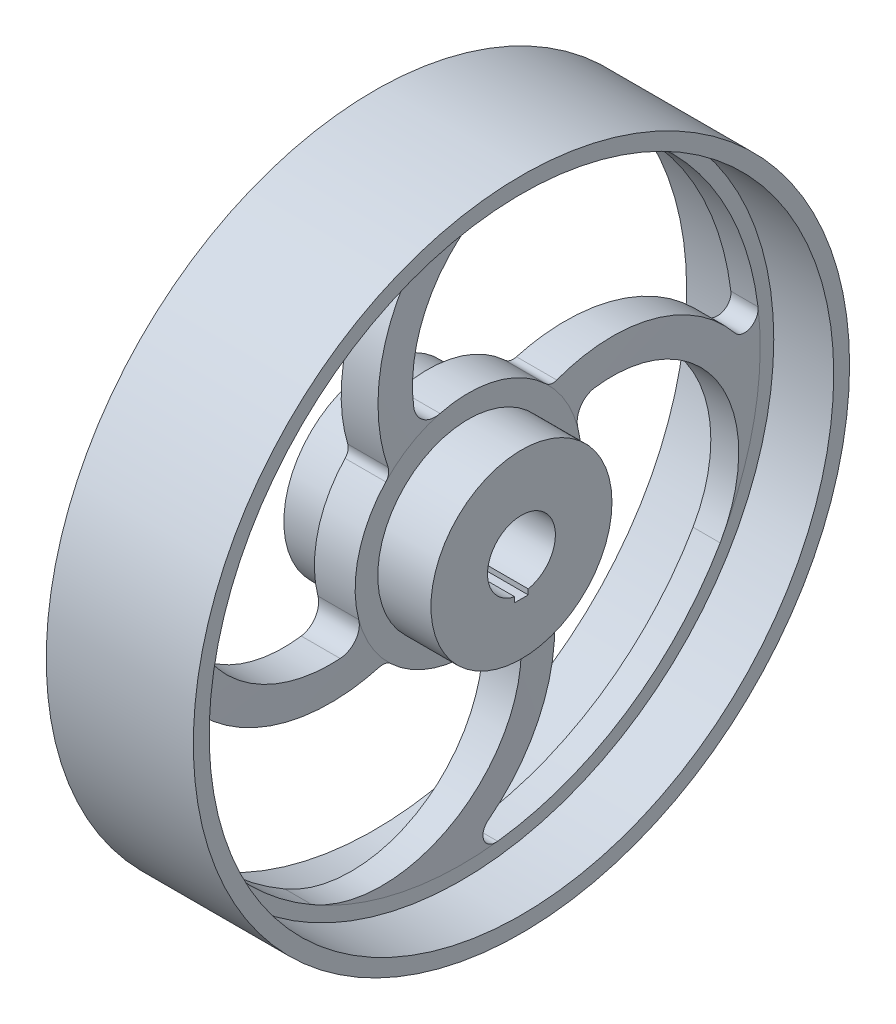
SolidWorks part; units mm, degrees
ref_plane "Front Plane" through (0, 0, 0) normal (0, 0, 1) x (1, 0, 0)
ref_plane "Top Plane" through (0, 0, 0) normal (0, 1, 0) x (1, 0, 0)
ref_plane "Right Plane" through (0, 0, 0) normal (1, 0, 0) x (0, 0, -1)
sketch "Sketch1" plane through (0, 0, 0) normal (0, 0, 1) x (1, 0, 0)
  line L0 (-32.5, 0) -> (32.5, 0)
  line L1 (-32.5, 15) -> (32.5, 15)
  line L2 (0, 0) -> (0, 138) construction
  line L3 (32.5, 15) -> (-32.5, 15)
  line L4 (32.5, 15) -> (32.5, 40)
  line L5 (32.5, 40) -> (-32.5, 40)
  line L6 (-32.5, 15) -> (-32.5, 40)
  line L7 (9, 30) -> (-9, 30)
  line L8 (9, 30) -> (9, 50)
  line L9 (9, 50) -> (-9, 50)
  line L10 (-9, 30) -> (-9, 50)
  line L11 (9, 30) -> (-9, 50) construction
  line L12 (9, 50) -> (-9, 30) construction
  line L13 (-6, 132) -> (-9, 50)
  line L14 (-32.5, 138) -> (32.5, 138)
  line L15 (-32.5, 138) -> (-32.5, 145)
  line L16 (-32.5, 145) -> (32.5, 145)
  line L17 (32.5, 138) -> (32.5, 145)
  line L18 (-32.5, 138) -> (32.5, 145) construction
  line L19 (-32.5, 145) -> (32.5, 138) construction
  line L20 (6, 144) -> (-6, 144)
  line L21 (6, 144) -> (6, 132)
  line L22 (6, 132) -> (-6, 132)
  line L23 (-6, 144) -> (-6, 132)
  line L24 (6, 144) -> (-6, 132) construction
  line L25 (6, 132) -> (-6, 144) construction
  line L26 (6, 132) -> (9, 50)
  point P4 (0, 0)
  point P9 (0, 40)
  point P14 (0, 141.5)
  point P17 (0, 95.0271)
  dimension "D1" = 65
  dimension "D3" = 25
  dimension "D4" = 18
  dimension "D5" = 20
  dimension "D6" = 138
  dimension "D7" = 65
  dimension "D8" = 12
  dimension "D9" = 12
  dimension "D10" = 7
  dimension "D11" = 145
  dimension "D2" = 15
revolve "Revolve2" add sketch "Sketch1" angle 360 about L0
sketch "Sketch3" plane through (0, 0, 0) normal (1, 0, 0) x (0, 0, -1)
  line L0 (0, 0) -> (0, 132) construction
  line L1 (0, 0) -> (66, 114.3154) construction
  circle A1 centre (0, 0) radius 50
  circle A2 centre (0, 0) radius 72 construction
  arc A3 (66, 114.3154) -> (-23.6846, 56.2095) centre (36, 62.3538) ccw
  arc A4 (-11.4606, 120.427) -> (-35.3353, 39.1963) centre (36, 62.3538) ccw
  arc A5 (-11.4606, 120.427) -> (-15.984, 131.0287) centre (-15.2575, 125.0728) ccw
  arc A6 (-23.6846, 56.2095) -> (-12.4846, 48.4163) centre (-14.7319, 57.1312) ccw
  arc A7 (-36.4464, 34.2295) -> (-35.3353, 39.1963) centre (-40.091, 37.6525) ccw
  arc A8 (114.3154, -66) -> (56.2095, 23.6846) centre (62.3538, -36) ccw
  arc A9 (120.427, 11.4606) -> (39.1963, 35.3353) centre (62.3538, -36) ccw
  arc A10 (56.2095, 23.6846) -> (48.4163, 12.4846) centre (57.1312, 14.7319) ccw
  arc A11 (34.2295, 36.4464) -> (39.1963, 35.3353) centre (37.6525, 40.091) ccw
  arc A12 (131.0287, 15.984) -> (66, 114.3154) centre (0, 0) ccw
  arc A13 (120.427, 11.4606) -> (131.0287, 15.984) centre (125.0728, 15.2575) ccw
  arc A14 (-66, -114.3154) -> (23.6846, -56.2095) centre (-36, -62.3538) ccw
  arc A15 (11.4606, -120.427) -> (35.3353, -39.1963) centre (-36, -62.3538) ccw
  arc A16 (23.6846, -56.2095) -> (12.4846, -48.4163) centre (14.7319, -57.1312) ccw
  arc A17 (36.4464, -34.2295) -> (35.3353, -39.1963) centre (40.091, -37.6525) ccw
  arc A18 (15.984, -131.0287) -> (114.3154, -66) centre (0, 0) ccw
  arc A19 (11.4606, -120.427) -> (15.984, -131.0287) centre (15.2575, -125.0728) ccw
  arc A20 (-114.3154, 66) -> (-56.2095, -23.6846) centre (-62.3538, 36) ccw
  arc A21 (-120.427, -11.4606) -> (-39.1963, -35.3353) centre (-62.3538, 36) ccw
  arc A22 (-56.2095, -23.6846) -> (-48.4163, -12.4846) centre (-57.1312, -14.7319) ccw
  arc A23 (-34.2295, -36.4464) -> (-39.1963, -35.3353) centre (-37.6525, -40.091) ccw
  arc A24 (-131.0287, -15.984) -> (-66, -114.3154) centre (0, 0) ccw
  arc A25 (-120.427, -11.4606) -> (-131.0287, -15.984) centre (-125.0728, -15.2575) ccw
  arc A26 (-15.984, 131.0287) -> (-114.3154, 66) centre (0, 0) ccw
  point P52 (0, 0)
  dimension "D3" = 100
  dimension "D4" = 120
  dimension "D5" = 150
  dimension "D6" = 6
  dimension "D7" = 9
  dimension "D8" = 5
  dimension "D10" = 264
  dimension "D1" = 30
  dimension "D9" = 4
extrude "Cut-Extrude2" cut sketch "Sketch3" along normal mid plane 50 contours A9 A13 A12 A3 A6 A1 A11 | A15 A19 A18 A8 A10 A1 A17 | A21 A25 A24 A14 A16 A1 A23 | A5 A26 A20 A22 A1 A7 A4
sketch "Sketch4" plane through (32.5, 0, 0) normal (1, 0, 0) x (0, 0, -1)
  line L1 (3, -13) -> (-3, -13)
  line L2 (3, -13) -> (3, -17)
  line L3 (3, -17) -> (-3, -17)
  line L4 (-3, -13) -> (-3, -17)
  line L5 (3, -13) -> (-3, -17) construction
  line L6 (3, -17) -> (-3, -13) construction
  circle A0 centre (0, 0) radius 15 construction
  point P0 (0, -15)
  dimension "D1" = 6
  dimension "D2" = 4
extrude "Cut-Extrude3" cut sketch "Sketch4" against normal blind 80
